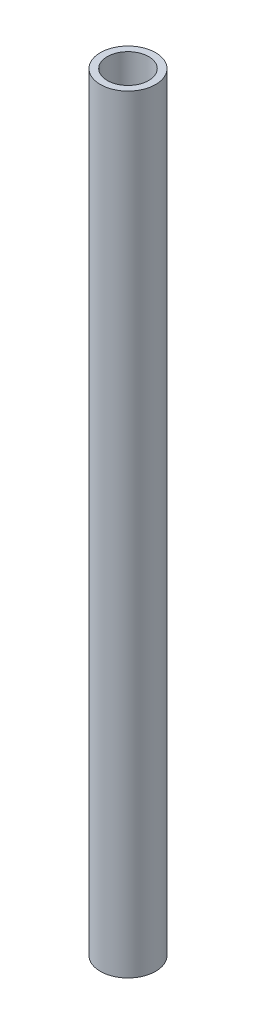
SolidWorks part; units mm, degrees
material "Brass"
ref_plane "Front Plane" through (0, 0, 0) normal (0, 0, 1) x (1, 0, 0)
ref_plane "Top Plane" through (0, 0, 0) normal (0, 1, 0) x (1, 0, 0)
ref_plane "Right Plane" through (0, 0, 0) normal (1, 0, 0) x (0, 0, -1)
sketch "Sketch1" plane through (0, 0, 0) normal (0, 1, 0) x (1, 0, 0)
  circle A0 centre (0, 0) radius 0.5
  dimension "D1" = 1
extrude "Boss-Extrude1" add sketch "Sketch1" along normal blind 13.9
hole_wizard "Ø0.4 (0.4) Diameter Hole1" positions "Sketch3" profile "Sketch2" hole size "Ø0.4" standard "Ansi Metric" end condition through all
sketch "Sketch3" plane through (0, 13.9, 0) normal (0, 1, 0) x (-1, 0, 0)
  point P0 (0, 0)
sketch "Sketch2" plane through (0, 13.9, 0) normal (1, 0, 0) x (0, 0, 1)
  line L0 (0, 0) -> (0, 13.9)
  line L1 (0, 13.9) -> (0.2, 13.9)
  line L2 (0.2, 13.9) -> (0.2, 0)
  line L5 (0.2, 0) -> (0, 0)
  line L11 (0, -6.35) -> (0, 107.95) construction
  dimension "Thru Hole Dia." = 0.4
  dimension "Thru Hole Depth" = 13.9
hole_wizard "Ø0.75 (0.75) Diameter Hole2" positions "Sketch5" profile "Sketch4" hole size "Ø0.75" standard "ANSI Metric"
sketch "Sketch5" plane through (0, 13.9, 0) normal (0, 1, 0) x (-1, 0, 0)
  point P0 (0, 0)
sketch "Sketch4" plane through (0, 13.9, 0) normal (1, 0, 0) x (0, 0, 1)
  line L0 (0, 0) -> (0, 11.5503)
  line L1 (0, 11.5503) -> (0.375, 11.325)
  line L2 (0.375, 11.325) -> (0.375, 0)
  line L5 (0.375, 0) -> (0, 0)
  line L10 (0, 11.5503) -> (-0.375, 11.325) construction
  line L11 (0, -6.35) -> (0, 107.95) construction
  dimension "Hole Dia." = 0.75
  dimension "Hole Depth" = 11.325
  dimension "Drill Angle" = 118
hole_wizard "Ø0.6 (0.6) Diameter Hole4" positions "Sketch7" profile "Sketch6" hole size "Ø0.6" standard "ANSI Metric"
sketch "Sketch7" plane through (0, 0, 0) normal (0, -1, 0) x (1, 0, 0)
  point P0 (0, 0)
sketch "Sketch6" plane through (0, 0, 0) normal (1, 0, 0) x (0, 0, -1)
  line L0 (0, 0) -> (0, 2.6053)
  line L1 (0, 2.6053) -> (0.3, 2.425)
  line L2 (0.3, 2.425) -> (0.3, 0)
  line L5 (0.3, 0) -> (0, 0)
  line L10 (0, 2.6053) -> (-0.3, 2.425) construction
  line L11 (0, -6.35) -> (0, 107.95) construction
  dimension "Hole Dia." = 0.6
  dimension "Hole Depth" = 2.425
  dimension "Drill Angle" = 118
